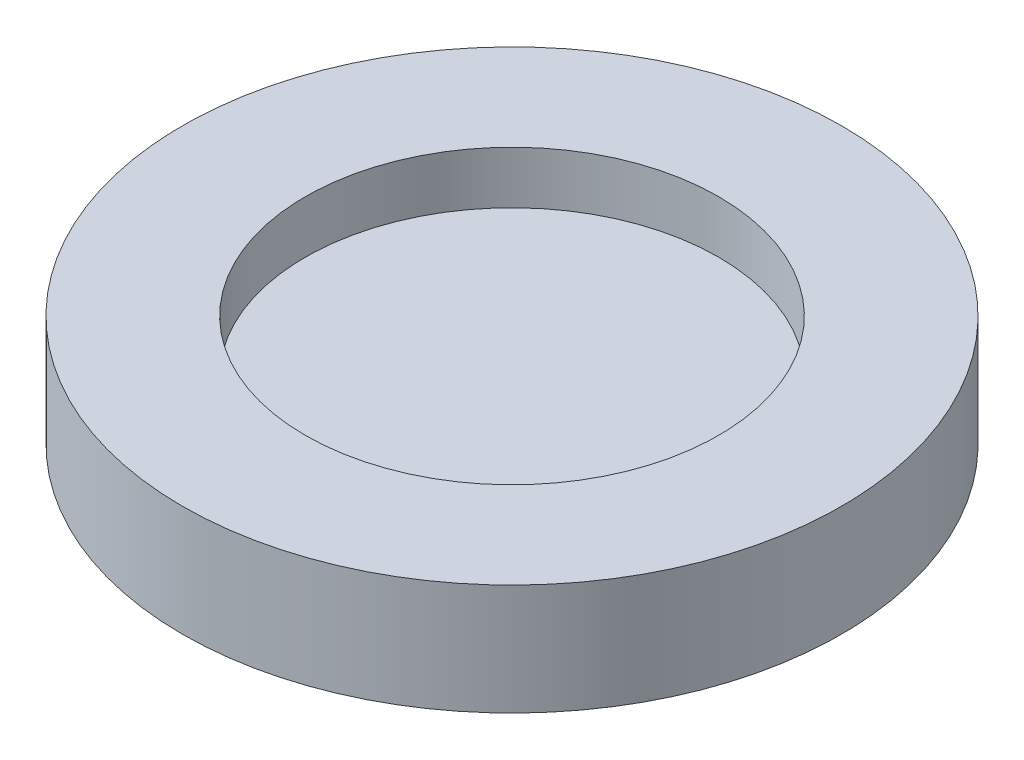
SolidWorks part; units mm, degrees
ref_plane "Front Plane" through (0, 0, 0) normal (0, 0, 1) x (1, 0, 0)
ref_plane "Top Plane" through (0, 0, 0) normal (0, 1, 0) x (1, 0, 0)
ref_plane "Right Plane" through (0, 0, 0) normal (1, 0, 0) x (0, 0, -1)
sketch "Sketch1" plane through (0, 0, 0) normal (0, 1, 0) x (1, 0, 0)
  circle A0 centre (0, 0) radius 11
  dimension "D1" = 22
extrude "Boss-Extrude1" add sketch "Sketch1" along normal blind 3.7
sketch "Sketch2" plane through (0, 3.7, 0) normal (0, 1, 0) x (1, 0, 0)
  circle A0 centre (0, 0) radius 6.9
  dimension "D1" = 13.8
extrude "Cut-Extrude1" cut sketch "Sketch2" against normal blind 3.7
ref_plane "Plane1" through (0, 1.85, 0) normal (0, 1, 0) x (1, 0, 0)
sketch "Sketch3" plane through (0, 1.85, 0) normal (0, 1, 0) x (1, 0, 0)
  circle A0 centre (0, 0) radius 8.7009
extrude "Boss-Extrude2" add sketch "Sketch3" along normal blind 0.1 and the other way blind 0.1
